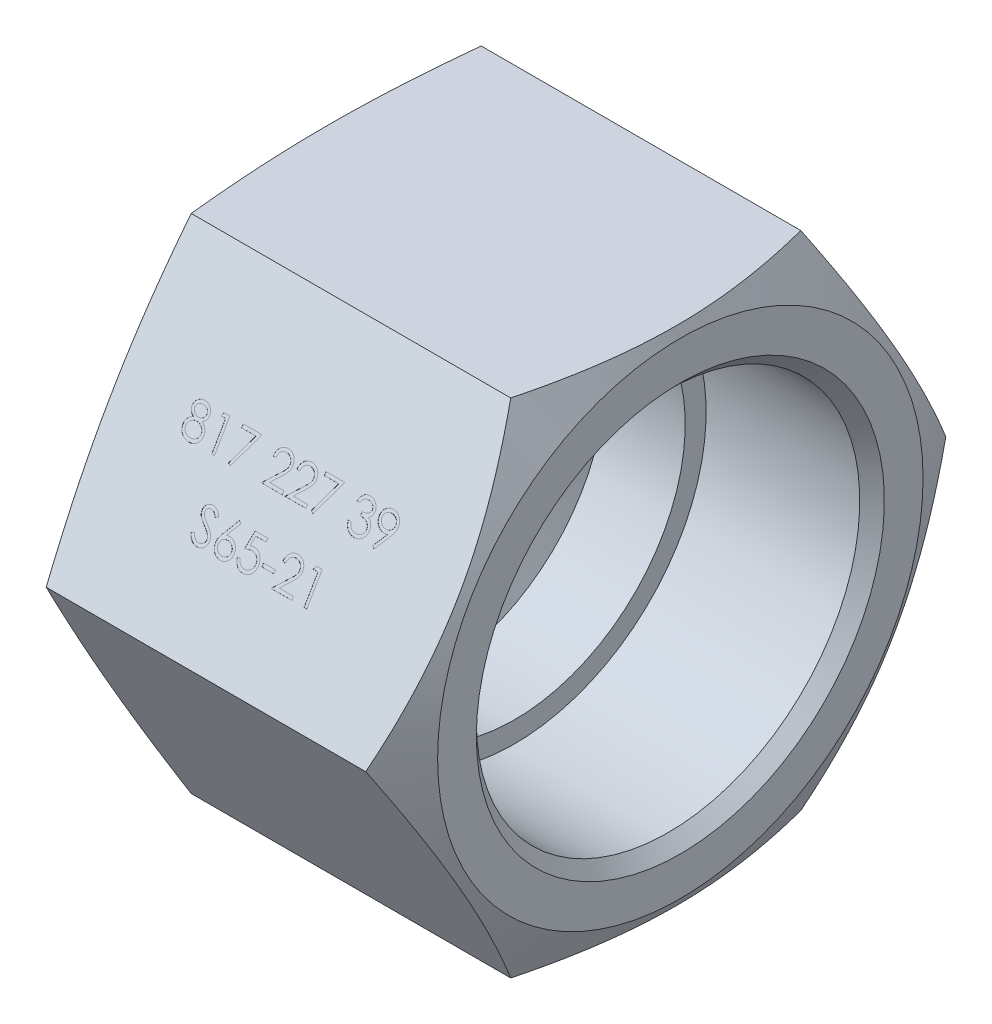
SolidWorks part; units mm, degrees
material "Plain Carbon Steel"
ref_plane "Front Plane" through (0, 0, 0) normal (0, 0, 1) x (1, 0, 0)
ref_plane "Top Plane" through (0, 0, 0) normal (0, 1, 0) x (1, 0, 0)
ref_plane "Right Plane" through (0, 0, 0) normal (1, 0, 0) x (0, 0, -1)
sketch "Sketch1" plane through (0, 0, 0) normal (0, 0, 1) x (1, 0, 0)
  line L0 (0, 0) -> (4, 0) construction
  line L1 (0, 0) -> (0, 14)
  line L2 (2, 23.6) -> (0, 14)
  line L3 (2, 23.6) -> (28, 23.6)
  line L4 (28, 23.6) -> (30, 19.75)
  line L5 (30, 19.75) -> (30, 15.6)
  line L6 (30, 15.6) -> (16.5, 15.6)
  line L7 (10, 13.9) -> (4, 1)
  line L8 (4, 1) -> (4, 0)
  line L9 (0, 0) -> (4, 0)
  line L10 (0, 0) -> (32.9705, 0) construction
  line L12 (10, 13.9) -> (16.5, 13.9)
  line L13 (16.5, 13.9) -> (16.5, 15.6)
  dimension "D1" = 27.8
  dimension "D2" = 26
  dimension "D3" = 30
  dimension "D4" = 28
  dimension "D5" = 47.2
  dimension "D7" = 2
  dimension "D6" = 2
  dimension "D8" = 31.2
  dimension "D9" = 20
  dimension "D10" = 2
  dimension "D11" = 39.5
  dimension "D12" = 13.5
revolve "Revolve1" add sketch "Sketch1" angle 360 about L0
cosmetic thread "Cosmetic Thread1" parameters "D1"=10, "D2"=33.8
sketch "Sketch2" plane through (30, 0, 0) normal (1, 0, 0) x (0, 0, -1)
  line L1 (11.8, 20.4382) -> (-11.8, 20.4382)
  line L2 (-11.8, 20.4382) -> (-23.6, 0)
  line L3 (-23.6, 0) -> (-11.8, -20.4382)
  line L4 (-11.8, -20.4382) -> (11.8, -20.4382)
  line L5 (11.8, -20.4382) -> (23.6, 0)
  line L6 (23.6, 0) -> (11.8, 20.4382)
  circle A0 centre (0, 0) radius 20.4382 construction
  circle A1 centre (0, 0) radius 23.6 construction
extrude "Extrude1" cut sketch "Sketch2" against normal up to surface (30 mm away) flip side to cut up to face at (0, 0, 14)
chamfer "Chamfer1" distance 1 angle 45 1 edges at (30, 0, 15.6)
sketch "Sketch3" plane through (0, 10.2191, 17.7) normal (0, 0.5, 0.866) x (1, 0, 0)
  line L0 (2.6188, 0) -> (28.2542, 0) construction
  text T0 "817 227 39\r\nS65-21"
extrude "Cut-Extrude1" cut sketch "Sketch3" against normal blind 0.01
